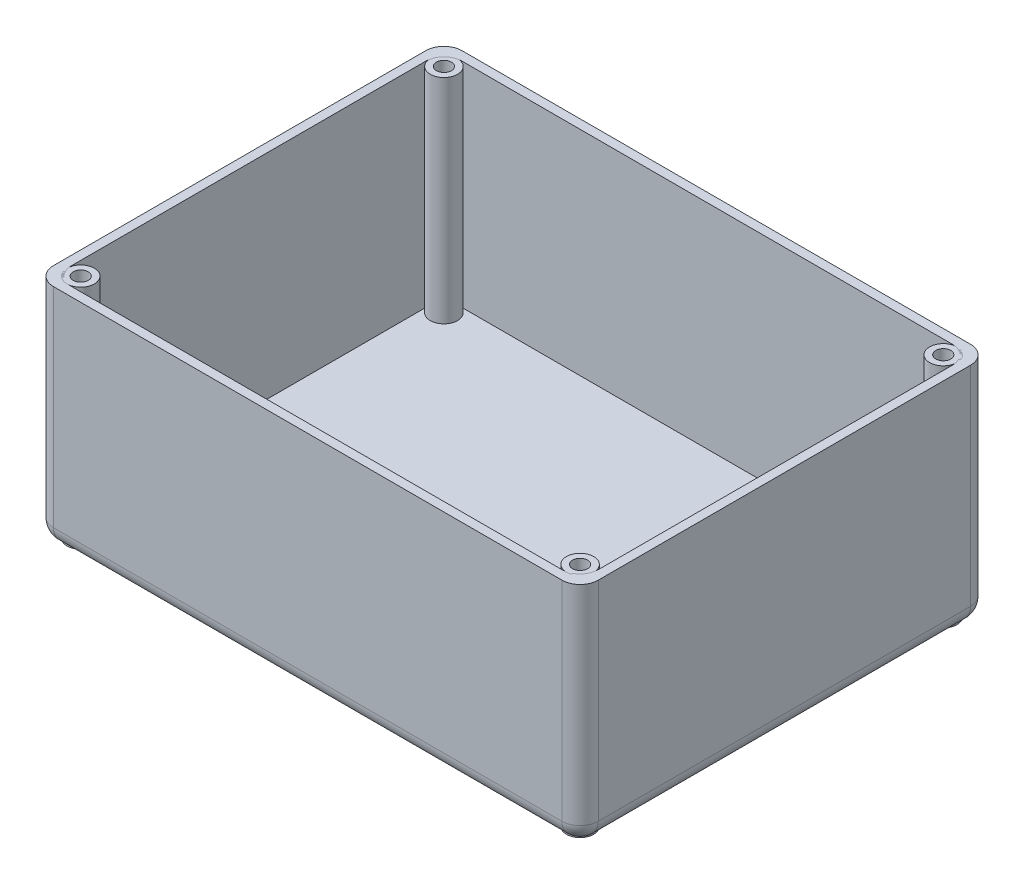
SolidWorks part; units mm, degrees
ref_plane "Front Plane" through (0, 0, 0) normal (0, 0, 1) x (1, 0, 0)
ref_plane "Top Plane" through (0, 0, 0) normal (0, 1, 0) x (1, 0, 0)
ref_plane "Right Plane" through (0, 0, 0) normal (1, 0, 0) x (0, 0, -1)
sketch "Sketch1" plane through (0, 0, 0) normal (0, 1, 0) x (1, 0, 0)
  line L1 (-75.0785, 33.4555) -> (44.9215, 33.4555)
  line L2 (-75.0785, 33.4555) -> (-75.0785, -56.5445)
  line L3 (-75.0785, -56.5445) -> (44.9215, -56.5445)
  line L4 (44.9215, 33.4555) -> (44.9215, -56.5445)
  dimension "D1" = 120
  dimension "D2" = 90
extrude "Boss-Extrude1" add sketch "Sketch1" along normal blind 50
sketch "Sketch2" plane through (0, 50, 0) normal (0, 1, 0) x (1, 0, 0)
  line L0 (44.9215, 33.4555) -> (-75.0785, 33.4555) construction
  line L1 (-73.0785, 31.4555) -> (42.9215, 31.4555)
  line L2 (-73.0785, 31.4555) -> (-73.0785, -54.5445)
  line L3 (-73.0785, -54.5445) -> (42.9215, -54.5445)
  line L4 (42.9215, 31.4555) -> (42.9215, -54.5445)
  line L5 (-75.0785, 33.4555) -> (-75.0785, -56.5445) construction
  dimension "D1" = 116
  dimension "D2" = 86
  dimension "D3" = 2
  dimension "D4" = 2
extrude "Cut-Extrude1" cut sketch "Sketch2" against normal blind 47
sketch "Sketch5" plane through (0, 0, 0) normal (0, -1, 0) x (1, 0, 0)
  line L0 (-75.0785, -33.4555) -> (-75.0785, 56.5445) construction
  line L1 (44.9215, -33.4555) -> (-75.0785, -33.4555) construction
  line L2 (-75.0785, 56.5445) -> (44.9215, 56.5445) construction
  line L3 (44.9215, 56.5445) -> (44.9215, -33.4555) construction
  circle A0 centre (-70.0785, -28.4555) radius 1.65
  circle A1 centre (-70.0785, 51.5445) radius 1.65
  circle A2 centre (39.9215, 51.5445) radius 3
  circle A3 centre (39.9215, -28.4555) radius 1.65
  circle A4 centre (-70.0785, -28.4555) radius 3
  circle A5 centre (-70.0785, 51.5445) radius 3
  circle A6 centre (39.9215, 51.5445) radius 1.65
  circle A7 centre (39.9215, -28.4555) radius 3
  dimension "D1" = 3.3
  dimension "D2" = 6
  dimension "D3" = 3.3
  dimension "D4" = 6
  dimension "D5" = 3.3
  dimension "D6" = 6
  dimension "D7" = 3.3
  dimension "D8" = 6
  dimension "D9" = 5
  dimension "D10" = 5
  dimension "D11" = 5
  dimension "D12" = 5
  dimension "D13" = 5
  dimension "D14" = 5
  dimension "D15" = 5
  dimension "D16" = 5
extrude "Boss-Extrude5" add sketch "Sketch5" against normal blind 50 separate body
fillet "Fillet1" radius 4 4 edges at (44.9215, 25, -33.4555) (44.9215, 25, 56.5445) (-75.0785, 25, 56.5445) (-75.0785, 25, -33.4555)
fillet "Fillet2" radius 4 8 edges at (-73.907, 0, -32.2839) (-15.0785, 0, -33.4555) (43.7499, 0, -32.2839) (44.9215, 0, 11.5445) (43.7499, 0, 55.3729) (-15.0785, 0, 56.5445) (-73.907, 0, 55.3729) (-75.0785, 0, 11.5445)
fillet "Fillet3" radius 4 4 edges at (-73.0785, 26.5, -31.4555) (-73.0785, 26.5, 54.5445) (42.9215, 26.5, 54.5445) (42.9215, 26.5, -31.4555)
